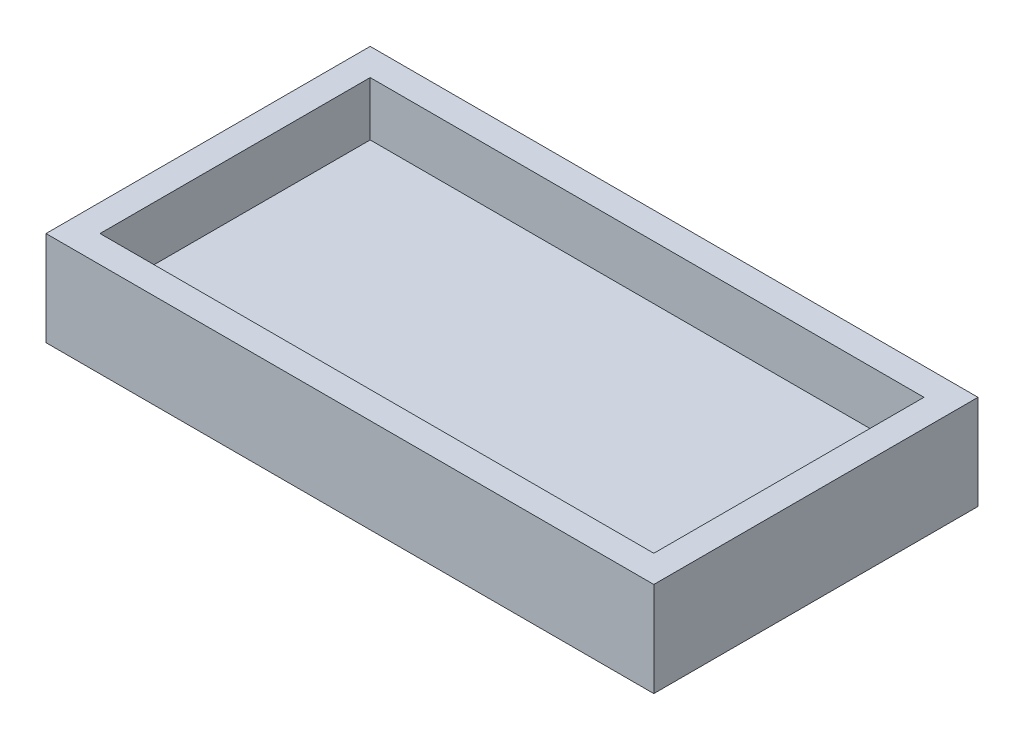
SolidWorks part; units mm, degrees
ref_plane "Front Plane" through (0, 0, 0) normal (0, 0, 1) x (1, 0, 0)
ref_plane "Top Plane" through (0, 0, 0) normal (0, 1, 0) x (1, 0, 0)
ref_plane "Right Plane" through (0, 0, 0) normal (1, 0, 0) x (0, 0, -1)
sketch "Sketch1" plane through (0, 0, 0) normal (0, 1, 0) x (1, 0, 0)
  line L1 (-20.5, 10) -> (20.5, 10)
  line L2 (-20.5, 10) -> (-20.5, -10)
  line L3 (-20.5, -10) -> (20.5, -10)
  line L4 (20.5, 10) -> (20.5, -10)
  line L5 (-20.5, 10) -> (20.5, -10) construction
  line L6 (-20.5, -10) -> (20.5, 10) construction
  point P0 (0, 0)
extrude "Boss-Extrude1" add sketch "Sketch1" along normal blind 3
sketch "Sketch2" plane through (0, 0, 0) normal (0, -1, 0) x (1, 0, 0)
  line L0 (-20.5, -10) -> (-20.5, 10) construction
  line L1 (20.5, -10) -> (-20.5, -10)
  line L2 (20.5, -10) -> (20.5, 10)
  line L3 (20.5, 10) -> (-20.5, 10)
  line L4 (-20.5, -10) -> (-20.5, 10)
  line L9 (22.5, -12) -> (22.5, 12)
  line L14 (22.5, 12) -> (-22.5, 12)
  line L15 (-22.5, -12) -> (-22.5, 12)
  line L16 (22.5, -12) -> (-22.5, -12)
  dimension "D2" = 2
extrude "Boss-Extrude2" add sketch "Sketch2" against normal offset from surface (7 mm away) 4 up to face at (0, 3, 0) offset beyond the face yes
